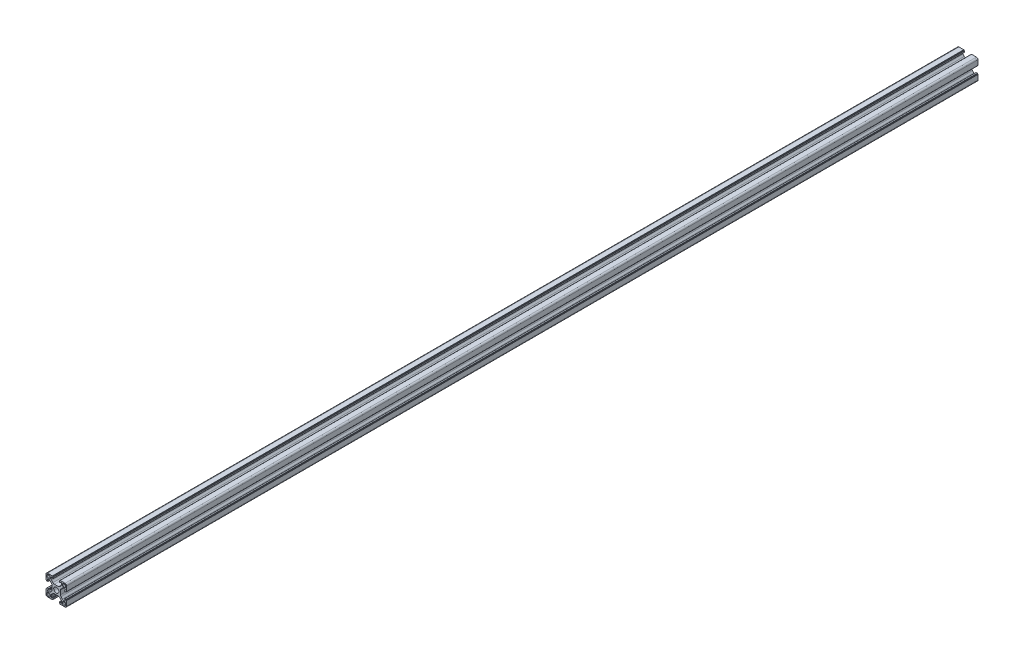
SolidWorks part; units mm, degrees
material "1060 Сплав"
ref_plane "Спереди" through (0, 0, 0) normal (0, 0, 1) x (1, 0, 0)
ref_plane "Сверху" through (0, 0, 0) normal (0, 1, 0) x (1, 0, 0)
ref_plane "Справа" through (0, 0, 0) normal (1, 0, 0) x (0, 0, -1)
sketch "Эскиз2" plane through (0, 0, 0) normal (0, 0, 1) x (1, 0, 0)
  line L0 (9.2299, 9.7837) -> (6.2299, 6.7837) construction
  line L1 (0.1299, 4.6837) -> (2.0286, 4.6837)
  line L2 (0.1299, 0.6837) -> (10.1299, 10.6837) construction
  line L3 (7.7299, 8.2837) -> (6.2299, 9.7837) construction
  line L4 (3.4428, 5.2695) -> (4.7441, 6.5707)
  line L5 (7.0299, 6.7837) -> (8.4299, 6.7837)
  line L6 (6.2299, 7.5837) -> (6.2299, 8.9837)
  line L7 (8.4299, 9.7837) -> (7.0299, 9.7837)
  line L8 (5.3299, 8.8837) -> (5.3299, 7.9849)
  line L9 (3.8931, 8.757) -> (4.3734, 9.2373)
  line L10 (3.3299, 10.2328) -> (3.8299, 10.2328)
  line L11 (3.7163, 8.6837) -> (3.4299, 8.6837)
  line L12 (4.727, 9.3837) -> (4.8299, 9.3837)
  line L13 (3.8299, 10.5337) -> (3.8299, 10.2328)
  line L14 (3.1799, 10.0828) -> (3.1799, 8.9337)
  line L15 (8.6299, 10.6837) -> (3.9799, 10.6837)
  line L16 (9.2299, 8.9837) -> (9.2299, 7.5837)
  line L17 (10.1299, 9.1837) -> (10.1299, 4.5337)
  line L18 (9.5289, 3.7337) -> (8.3799, 3.7337)
  line L19 (9.9799, 4.3837) -> (9.6789, 4.3837)
  line L20 (8.8299, 5.2808) -> (8.8299, 5.3837)
  line L21 (8.1299, 4.2702) -> (8.1299, 3.9837)
  line L22 (9.6789, 3.8837) -> (9.6789, 4.3837)
  line L23 (8.2031, 4.447) -> (8.6834, 4.9273)
  line L24 (8.3299, 5.8837) -> (7.4311, 5.8837)
  line L25 (4.7156, 3.9967) -> (6.0169, 5.2979)
  line L26 (4.1299, 0.6837) -> (4.1299, 2.5825)
  line L27 (4.1299, 0.6837) -> (4.1299, -1.2151)
  line L28 (4.7156, -2.6293) -> (6.0169, -3.9305)
  line L29 (6.2299, -6.2163) -> (6.2299, -7.6163)
  line L30 (7.0299, -5.4163) -> (8.4299, -5.4163)
  line L31 (9.2299, -7.6163) -> (9.2299, -6.2163)
  line L32 (8.3299, -4.5163) -> (7.4311, -4.5163)
  line L33 (8.2031, -3.0795) -> (8.6834, -3.5598)
  line L34 (9.6789, -2.5163) -> (9.6789, -3.0163)
  line L35 (8.1299, -2.9027) -> (8.1299, -2.6163)
  line L36 (8.8299, -3.9134) -> (8.8299, -4.0163)
  line L37 (9.9799, -3.0163) -> (9.6789, -3.0163)
  line L38 (9.5289, -2.3663) -> (8.3799, -2.3663)
  line L39 (10.1299, -7.8163) -> (10.1299, -3.1663)
  line L40 (8.4299, -8.4163) -> (7.0299, -8.4163)
  line L41 (8.6299, -9.3163) -> (3.9799, -9.3163)
  line L42 (3.1799, -8.7153) -> (3.1799, -7.5663)
  line L43 (3.8299, -9.1663) -> (3.8299, -8.8653)
  line L44 (4.727, -8.0163) -> (4.8299, -8.0163)
  line L45 (3.7163, -7.3163) -> (3.4299, -7.3163)
  line L46 (3.3299, -8.8653) -> (3.8299, -8.8653)
  line L47 (3.8931, -7.3895) -> (4.3734, -7.8698)
  line L48 (5.3299, -7.5163) -> (5.3299, -6.6175)
  line L49 (3.4428, -3.9021) -> (4.7441, -5.2033)
  line L50 (0.1299, -3.3163) -> (2.0286, -3.3163)
  line L51 (9.2299, -8.4163) -> (6.2299, -5.4163) construction
  line L52 (0.1299, 0.6837) -> (10.1299, -9.3163) construction
  line L53 (7.7299, -6.9163) -> (9.2299, -5.4163) construction
  line L54 (0.1299, -3.3163) -> (-1.7689, -3.3163)
  line L55 (-3.1831, -3.9021) -> (-4.4844, -5.2033)
  line L56 (-6.7701, -5.4163) -> (-8.1701, -5.4163)
  line L57 (-5.9701, -6.2163) -> (-5.9701, -7.6163)
  line L58 (-8.1701, -8.4163) -> (-6.7701, -8.4163)
  line L59 (-5.0701, -7.5163) -> (-5.0701, -6.6175)
  line L60 (-3.6334, -7.3895) -> (-4.1137, -7.8698)
  line L61 (-3.0701, -8.8653) -> (-3.5701, -8.8653)
  line L62 (-3.4566, -7.3163) -> (-3.1701, -7.3163)
  line L63 (-4.4673, -8.0163) -> (-4.5701, -8.0163)
  line L64 (-3.5701, -9.1663) -> (-3.5701, -8.8653)
  line L65 (-2.9201, -8.7153) -> (-2.9201, -7.5663)
  line L66 (-8.3701, -9.3163) -> (-3.7201, -9.3163)
  line L67 (-8.9701, -7.6163) -> (-8.9701, -6.2163)
  line L68 (-9.8701, -7.8163) -> (-9.8701, -3.1663)
  line L69 (-9.2692, -2.3663) -> (-8.1201, -2.3663)
  line L70 (-9.7201, -3.0163) -> (-9.4192, -3.0163)
  line L71 (-8.5701, -3.9134) -> (-8.5701, -4.0163)
  line L72 (-7.8701, -2.9027) -> (-7.8701, -2.6163)
  line L73 (-9.4192, -2.5163) -> (-9.4192, -3.0163)
  line L74 (-7.9434, -3.0795) -> (-8.4237, -3.5598)
  line L75 (-8.0701, -4.5163) -> (-7.1714, -4.5163)
  line L76 (-4.4559, -2.6293) -> (-5.7572, -3.9305)
  line L77 (-3.8701, 0.6837) -> (-3.8701, -1.2151)
  line L78 (-8.9701, -8.4163) -> (-5.9701, -5.4163) construction
  line L79 (0.1299, 0.6837) -> (-9.8701, -9.3163) construction
  line L80 (-7.4701, -6.9163) -> (-5.9701, -8.4163) construction
  line L81 (-3.8701, 0.6837) -> (-3.8701, 2.5825)
  line L82 (-4.4559, 3.9967) -> (-5.7572, 5.2979)
  line L83 (-5.9701, 7.5837) -> (-5.9701, 8.9837)
  line L84 (-6.7701, 6.7837) -> (-8.1701, 6.7837)
  line L85 (-8.9701, 8.9837) -> (-8.9701, 7.5837)
  line L86 (-8.0701, 5.8837) -> (-7.1714, 5.8837)
  line L87 (-7.9434, 4.447) -> (-8.4237, 4.9273)
  line L88 (-9.4192, 3.8837) -> (-9.4192, 4.3837)
  line L89 (-7.8701, 4.2702) -> (-7.8701, 3.9837)
  line L90 (-8.5701, 5.2808) -> (-8.5701, 5.3837)
  line L91 (-9.7201, 4.3837) -> (-9.4192, 4.3837)
  line L92 (-9.2692, 3.7337) -> (-8.1201, 3.7337)
  line L93 (-9.8701, 9.1837) -> (-9.8701, 4.5337)
  line L94 (-8.1701, 9.7837) -> (-6.7701, 9.7837)
  line L95 (-8.3701, 10.6837) -> (-3.7201, 10.6837)
  line L96 (-2.9201, 10.0828) -> (-2.9201, 8.9337)
  line L97 (-3.5701, 10.5337) -> (-3.5701, 10.2328)
  line L98 (-4.4673, 9.3837) -> (-4.5701, 9.3837)
  line L99 (-3.4566, 8.6837) -> (-3.1701, 8.6837)
  line L100 (-3.0701, 10.2328) -> (-3.5701, 10.2328)
  line L101 (-3.6334, 8.757) -> (-4.1137, 9.2373)
  line L102 (-5.0701, 8.8837) -> (-5.0701, 7.9849)
  line L103 (-3.1831, 5.2695) -> (-4.4844, 6.5707)
  line L104 (0.1299, 4.6837) -> (-1.7689, 4.6837)
  line L105 (-11.6342, 0.6837) -> (11.6342, 0.6837) construction
  line L106 (-8.9701, 9.7837) -> (-5.9701, 6.7837) construction
  line L107 (0.1299, -11.4027) -> (0.1299, 11.4027) construction
  line L108 (0.1299, 0.6837) -> (-9.8701, 10.6837) construction
  line L109 (-7.4701, 8.2837) -> (-8.9701, 6.7837) construction
  arc A0 (9.2299, 8.9837) -> (8.4299, 9.7837) centre (8.4299, 8.9837) ccw
  arc A1 (7.0299, 9.7837) -> (6.2299, 8.9837) centre (7.0299, 8.9837) ccw
  arc A2 (7.0299, 6.7837) -> (6.2299, 7.5837) centre (7.0299, 7.5837) cw
  arc A3 (8.6299, 10.6837) -> (10.1299, 9.1837) centre (8.6299, 9.1837) cw
  arc A4 (3.3299, 10.2328) -> (3.1799, 10.0828) centre (3.3299, 10.0828) ccw
  arc A5 (3.9799, 10.6837) -> (3.8299, 10.5337) centre (3.9799, 10.5337) ccw
  arc A6 (3.7163, 8.6837) -> (3.8931, 8.757) centre (3.7163, 8.9337) ccw
  arc A7 (3.4299, 8.6837) -> (3.1799, 8.9337) centre (3.4299, 8.9337) cw
  arc A8 (4.3734, 9.2373) -> (4.727, 9.3837) centre (4.727, 8.8837) cw
  arc A9 (4.8299, 9.3837) -> (5.3299, 8.8837) centre (4.8299, 8.8837) cw
  arc A10 (2.6299, 0.6837) -> (0.1299, 3.1837) centre (0.1299, 0.6837) ccw
  arc A11 (2.0286, 4.6837) -> (3.4428, 5.2695) centre (2.0286, 6.6837) ccw
  arc A12 (5.3299, 7.9849) -> (4.7441, 6.5707) centre (3.3299, 7.9849) cw
  arc A13 (9.2299, 7.5837) -> (8.4299, 6.7837) centre (8.4299, 7.5837) cw
  arc A14 (8.8299, 5.3837) -> (8.3299, 5.8837) centre (8.3299, 5.3837) ccw
  arc A15 (8.6834, 4.9273) -> (8.8299, 5.2808) centre (8.3299, 5.2808) ccw
  arc A16 (8.1299, 3.9837) -> (8.3799, 3.7337) centre (8.3799, 3.9837) ccw
  arc A17 (8.1299, 4.2702) -> (8.2031, 4.447) centre (8.3799, 4.2702) cw
  arc A18 (10.1299, 4.5337) -> (9.9799, 4.3837) centre (9.9799, 4.5337) cw
  arc A19 (9.6789, 3.8837) -> (9.5289, 3.7337) centre (9.5289, 3.8837) cw
  arc A20 (7.4311, 5.8837) -> (6.0169, 5.2979) centre (7.4311, 3.8837) ccw
  arc A21 (4.1299, 2.5825) -> (4.7156, 3.9967) centre (6.1299, 2.5825) cw
  arc A22 (8.4299, -8.4163) -> (9.2299, -7.6163) centre (8.4299, -7.6163) ccw
  arc A23 (9.2299, -6.2163) -> (8.4299, -5.4163) centre (8.4299, -6.2163) ccw
  arc A24 (6.2299, -6.2163) -> (7.0299, -5.4163) centre (7.0299, -6.2163) cw
  arc A25 (10.1299, -7.8163) -> (8.6299, -9.3163) centre (8.6299, -7.8163) cw
  arc A26 (9.6789, -2.5163) -> (9.5289, -2.3663) centre (9.5289, -2.5163) ccw
  arc A27 (10.1299, -3.1663) -> (9.9799, -3.0163) centre (9.9799, -3.1663) ccw
  arc A28 (8.1299, -2.9027) -> (8.2031, -3.0795) centre (8.3799, -2.9027) ccw
  arc A29 (8.1299, -2.6163) -> (8.3799, -2.3663) centre (8.3799, -2.6163) cw
  arc A30 (8.6834, -3.5598) -> (8.8299, -3.9134) centre (8.3299, -3.9134) cw
  arc A31 (8.8299, -4.0163) -> (8.3299, -4.5163) centre (8.3299, -4.0163) cw
  arc A32 (0.1299, -1.8163) -> (2.6299, 0.6837) centre (0.1299, 0.6837) ccw
  arc A33 (4.1299, -1.2151) -> (4.7156, -2.6293) centre (6.1299, -1.2151) ccw
  arc A34 (7.4311, -4.5163) -> (6.0169, -3.9305) centre (7.4311, -2.5163) cw
  arc A35 (7.0299, -8.4163) -> (6.2299, -7.6163) centre (7.0299, -7.6163) cw
  arc A36 (4.8299, -8.0163) -> (5.3299, -7.5163) centre (4.8299, -7.5163) ccw
  arc A37 (4.3734, -7.8698) -> (4.727, -8.0163) centre (4.727, -7.5163) ccw
  arc A38 (3.4299, -7.3163) -> (3.1799, -7.5663) centre (3.4299, -7.5663) ccw
  arc A39 (3.7163, -7.3163) -> (3.8931, -7.3895) centre (3.7163, -7.5663) cw
  arc A40 (3.9799, -9.3163) -> (3.8299, -9.1663) centre (3.9799, -9.1663) cw
  arc A41 (3.3299, -8.8653) -> (3.1799, -8.7153) centre (3.3299, -8.7153) cw
  arc A42 (5.3299, -6.6175) -> (4.7441, -5.2033) centre (3.3299, -6.6175) ccw
  arc A43 (2.0286, -3.3163) -> (3.4428, -3.9021) centre (2.0286, -5.3163) cw
  arc A44 (-8.9701, -7.6163) -> (-8.1701, -8.4163) centre (-8.1701, -7.6163) ccw
  arc A45 (-6.7701, -8.4163) -> (-5.9701, -7.6163) centre (-6.7701, -7.6163) ccw
  arc A46 (-6.7701, -5.4163) -> (-5.9701, -6.2163) centre (-6.7701, -6.2163) cw
  arc A47 (-8.3701, -9.3163) -> (-9.8701, -7.8163) centre (-8.3701, -7.8163) cw
  arc A48 (-3.0701, -8.8653) -> (-2.9201, -8.7153) centre (-3.0701, -8.7153) ccw
  arc A49 (-3.7201, -9.3163) -> (-3.5701, -9.1663) centre (-3.7201, -9.1663) ccw
  arc A50 (-3.4566, -7.3163) -> (-3.6334, -7.3895) centre (-3.4566, -7.5663) ccw
  arc A51 (-3.1701, -7.3163) -> (-2.9201, -7.5663) centre (-3.1701, -7.5663) cw
  arc A52 (-4.1137, -7.8698) -> (-4.4673, -8.0163) centre (-4.4673, -7.5163) cw
  arc A53 (-4.5701, -8.0163) -> (-5.0701, -7.5163) centre (-4.5701, -7.5163) cw
  arc A54 (-2.3701, 0.6837) -> (0.1299, -1.8163) centre (0.1299, 0.6837) ccw
  arc A55 (-1.7689, -3.3163) -> (-3.1831, -3.9021) centre (-1.7689, -5.3163) ccw
  arc A56 (-5.0701, -6.6175) -> (-4.4844, -5.2033) centre (-3.0701, -6.6175) cw
  arc A57 (-8.9701, -6.2163) -> (-8.1701, -5.4163) centre (-8.1701, -6.2163) cw
  arc A58 (-8.5701, -4.0163) -> (-8.0701, -4.5163) centre (-8.0701, -4.0163) ccw
  arc A59 (-8.4237, -3.5598) -> (-8.5701, -3.9134) centre (-8.0701, -3.9134) ccw
  arc A60 (-7.8701, -2.6163) -> (-8.1201, -2.3663) centre (-8.1201, -2.6163) ccw
  arc A61 (-7.8701, -2.9027) -> (-7.9434, -3.0795) centre (-8.1201, -2.9027) cw
  arc A62 (-9.8701, -3.1663) -> (-9.7201, -3.0163) centre (-9.7201, -3.1663) cw
  arc A63 (-9.4192, -2.5163) -> (-9.2692, -2.3663) centre (-9.2692, -2.5163) cw
  arc A64 (-7.1714, -4.5163) -> (-5.7572, -3.9305) centre (-7.1714, -2.5163) ccw
  arc A65 (-3.8701, -1.2151) -> (-4.4559, -2.6293) centre (-5.8701, -1.2151) cw
  arc A66 (-8.1701, 9.7837) -> (-8.9701, 8.9837) centre (-8.1701, 8.9837) ccw
  arc A67 (-8.9701, 7.5837) -> (-8.1701, 6.7837) centre (-8.1701, 7.5837) ccw
  arc A68 (-5.9701, 7.5837) -> (-6.7701, 6.7837) centre (-6.7701, 7.5837) cw
  arc A69 (-9.8701, 9.1837) -> (-8.3701, 10.6837) centre (-8.3701, 9.1837) cw
  arc A70 (-9.4192, 3.8837) -> (-9.2692, 3.7337) centre (-9.2692, 3.8837) ccw
  arc A71 (-9.8701, 4.5337) -> (-9.7201, 4.3837) centre (-9.7201, 4.5337) ccw
  arc A72 (-7.8701, 4.2702) -> (-7.9434, 4.447) centre (-8.1201, 4.2702) ccw
  arc A73 (-7.8701, 3.9837) -> (-8.1201, 3.7337) centre (-8.1201, 3.9837) cw
  arc A74 (-8.4237, 4.9273) -> (-8.5701, 5.2808) centre (-8.0701, 5.2808) cw
  arc A75 (-8.5701, 5.3837) -> (-8.0701, 5.8837) centre (-8.0701, 5.3837) cw
  arc A76 (0.1299, 3.1837) -> (-2.3701, 0.6837) centre (0.1299, 0.6837) ccw
  arc A77 (-3.8701, 2.5825) -> (-4.4559, 3.9967) centre (-5.8701, 2.5825) ccw
  arc A78 (-7.1714, 5.8837) -> (-5.7572, 5.2979) centre (-7.1714, 3.8837) cw
  arc A79 (-6.7701, 9.7837) -> (-5.9701, 8.9837) centre (-6.7701, 8.9837) cw
  arc A80 (-4.5701, 9.3837) -> (-5.0701, 8.8837) centre (-4.5701, 8.8837) ccw
  arc A81 (-4.1137, 9.2373) -> (-4.4673, 9.3837) centre (-4.4673, 8.8837) ccw
  arc A82 (-3.1701, 8.6837) -> (-2.9201, 8.9337) centre (-3.1701, 8.9337) ccw
  arc A83 (-3.4566, 8.6837) -> (-3.6334, 8.757) centre (-3.4566, 8.9337) cw
  arc A84 (-3.7201, 10.6837) -> (-3.5701, 10.5337) centre (-3.7201, 10.5337) cw
  arc A85 (-3.0701, 10.2328) -> (-2.9201, 10.0828) centre (-3.0701, 10.0828) cw
  arc A86 (-5.0701, 7.9849) -> (-4.4844, 6.5707) centre (-3.0701, 7.9849) ccw
  arc A87 (-1.7689, 4.6837) -> (-3.1831, 5.2695) centre (-1.7689, 6.6837) cw
  point P0 (0.1299, 0.6837)
  point P9 (0.1299, 0.6837)
  point P40 (8.8299, 4.3837)
  point P93 (3.8299, -8.0163)
  point P144 (3.8299, 9.3837)
  point P152 (8.8299, -3.0163)
  point P153 (0.1299, -3.2405)
  point P154 (0.1299, 0.6837)
  point P189 (-8.5701, -3.0163)
  point P228 (-3.5701, -8.0163)
  point P229 (-3.7944, 0.6837)
  point P230 (0.1299, 0.6837)
  point P268 (-3.5701, 9.3837)
  point P273 (4.0541, 0.6837)
  point P306 (-8.5701, 4.3837)
  point P307 (0.1299, 4.608)
  point P309 (0.1299, 0.6837)
  dimension "D3" = 5
  dimension "D6" = 2
  dimension "D1" = 2
  dimension "D2" = 6
  dimension "D4" = 4
  dimension "D5" = 0.9
extrude "Бобышка-Вытянуть1" add sketch "Эскиз2" along normal blind 885
